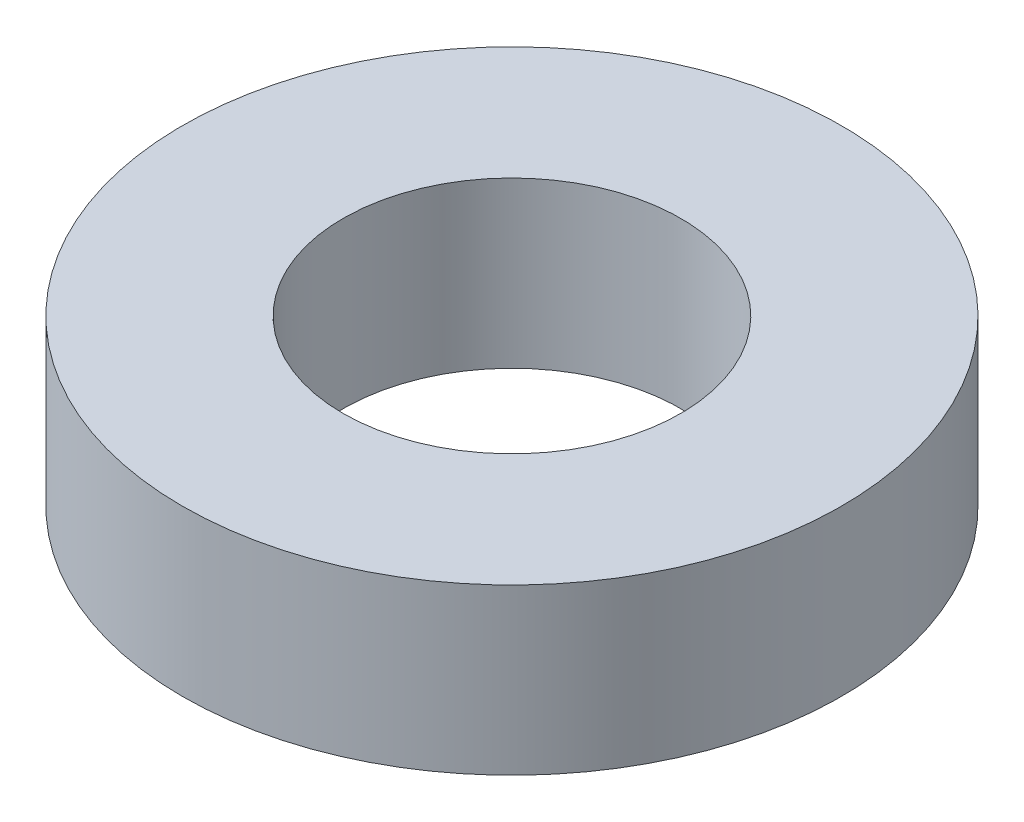
SolidWorks part; units mm, degrees
ref_plane "Спереди" through (0, 0, 0) normal (0, 0, 1) x (1, 0, 0)
ref_plane "Сверху" through (0, 0, 0) normal (0, 1, 0) x (1, 0, 0)
ref_plane "Справа" through (0, 0, 0) normal (1, 0, 0) x (0, 0, -1)
sketch "Эскиз1" plane through (0, 0, 0) normal (0, 1, 0) x (1, 0, 0)
  circle A0 centre (0, 0) radius 4.1
  circle A1 centre (0, 0) radius 8
extrude "Бобышка-Вытянуть1" add sketch "Эскиз1" along normal blind 4
